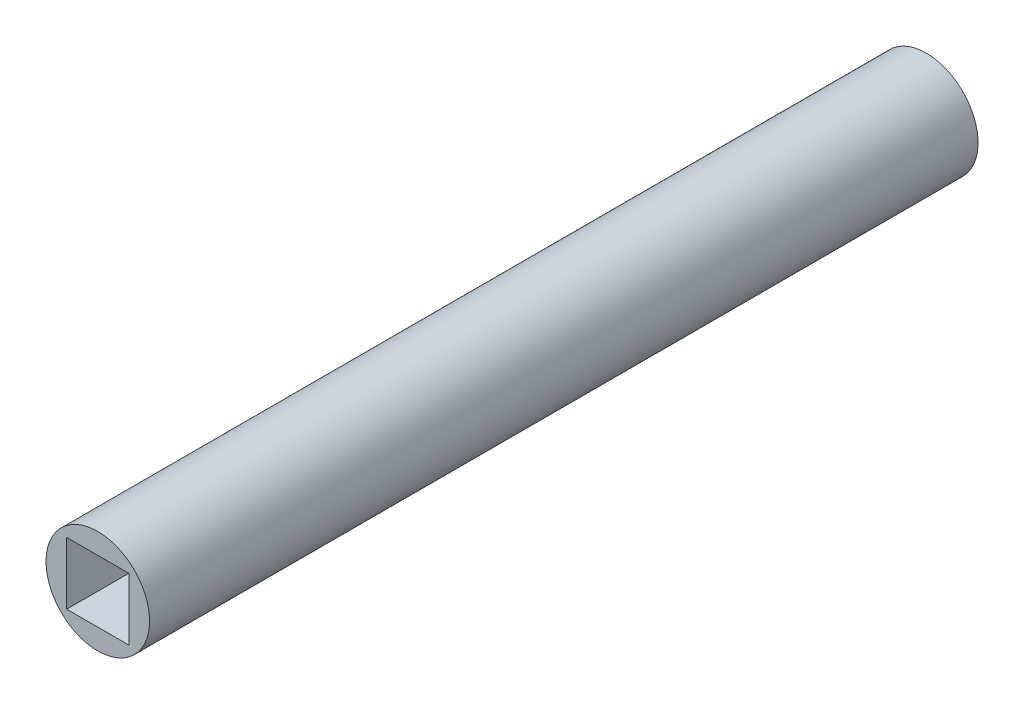
SolidWorks part; units mm, degrees
material "PLA"
ref_plane "Front Plane" through (0, 0, 0) normal (0, 0, 1) x (1, 0, 0)
ref_plane "Top Plane" through (0, 0, 0) normal (0, 1, 0) x (1, 0, 0)
ref_plane "Right Plane" through (0, 0, 0) normal (1, 0, 0) x (0, 0, -1)
sketch "Sketch1" plane through (0, 0, 0) normal (0, 1, 0) x (1, 0, 0)
  line L1 (0, 0) -> (-15.875, 0)
  line L2 (0, 0) -> (0, -254)
  line L3 (0, -254) -> (-15.875, -254)
  line L4 (-15.875, 0) -> (-15.875, -254)
  dimension "D1" = 254
  dimension "D2" = 15.875
revolve "Revolve1" add sketch "Sketch1" angle 360 about L2
sketch "Sketch2" plane through (0, 0, 254) normal (0, 0, 1) x (1, 0, 0)
  line L1 (-9.525, 9.525) -> (9.525, 9.525)
  line L2 (-9.525, 9.525) -> (-9.525, -9.525)
  line L3 (-9.525, -9.525) -> (9.525, -9.525)
  line L4 (9.525, 9.525) -> (9.525, -9.525)
  line L5 (-9.525, 9.525) -> (9.525, -9.525) construction
  line L6 (-9.525, -9.525) -> (9.525, 9.525) construction
  point P0 (0, 0)
  dimension "D1" = 19.05
  dimension "D2" = 19.05
extrude "Cut-Extrude1" cut sketch "Sketch2" against normal through all contours L2 L1 L4 L3
